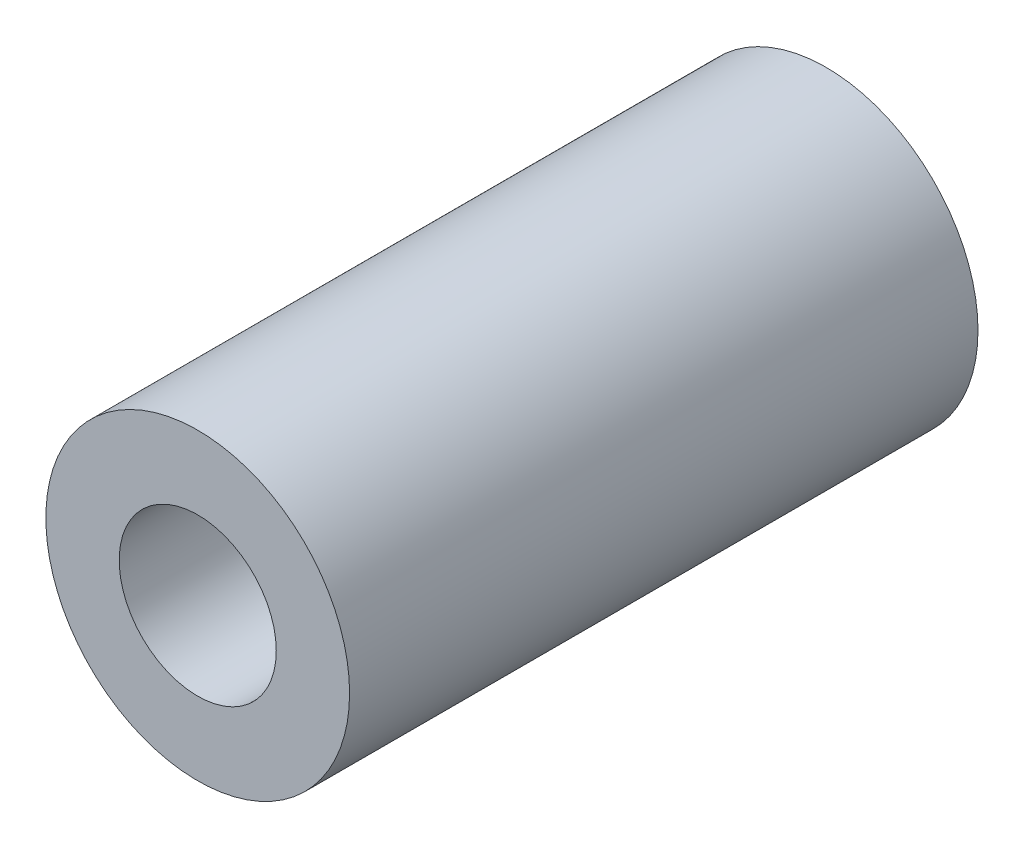
SolidWorks part; units mm, degrees
ref_plane "Alzado" through (0, 0, 0) normal (0, 0, 1) x (1, 0, 0)
ref_plane "Planta" through (0, 0, 0) normal (0, 1, 0) x (1, 0, 0)
ref_plane "Vista lateral" through (0, 0, 0) normal (1, 0, 0) x (0, 0, -1)
sketch "Croquis1" plane through (0, 0, 0) normal (0, 0, 1) x (1, 0, 0)
  circle A0 centre (0, 0) radius 1.5
  circle A1 centre (0, 0) radius 2.9
  dimension "D1" = 3
  dimension "D2" = 1.4
extrude "Saliente-Extruir1" add sketch "Croquis1" along normal blind 12
